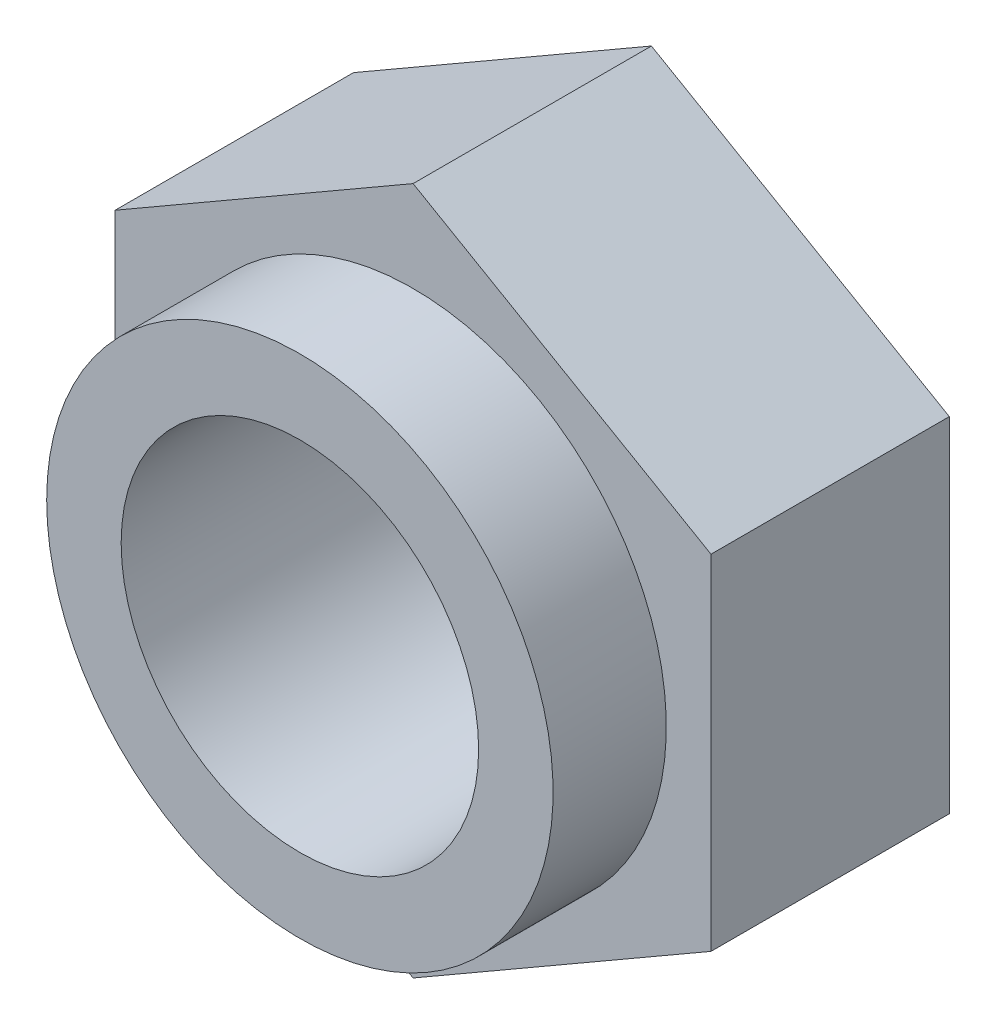
SolidWorks part; units mm, degrees
material "合金钢"
ref_plane "前视基准面" through (0, 0, 0) normal (0, 0, 1) x (1, 0, 0)
ref_plane "上视基准面" through (0, 0, 0) normal (0, 1, 0) x (1, 0, 0)
ref_plane "右视基准面" through (0, 0, 0) normal (1, 0, 0) x (0, 0, -1)
sketch "草图1" plane through (0, 0, 0) normal (0, 0, 1) x (1, 0, 0)
  line L1 (0, 5.7735) -> (-5, 2.8868)
  line L2 (-5, 2.8868) -> (-5, -2.8868)
  line L3 (-5, -2.8868) -> (0, -5.7735)
  line L4 (0, -5.7735) -> (5, -2.8868)
  line L5 (5, -2.8868) -> (5, 2.8868)
  line L6 (5, 2.8868) -> (0, 5.7735)
  circle A0 centre (0, 0) radius 5 construction
  dimension "D1" = 10
extrude "凸台-拉伸1" add sketch "草图1" along normal blind 4
sketch "草图2" plane through (0, 0, 4) normal (0, 0, 1) x (1, 0, 0)
  circle A0 centre (0, 0) radius 4.25
  dimension "D1" = 8.5
extrude "凸台-拉伸2" add sketch "草图2" along normal blind 1.9
sketch "草图3" plane through (0, 0, 5.9) normal (0, 0, 1) x (1, 0, 0)
  circle A0 centre (0, 0) radius 3
  dimension "D1" = 6
extrude "切除-拉伸1" cut sketch "草图3" against normal blind 9.9
